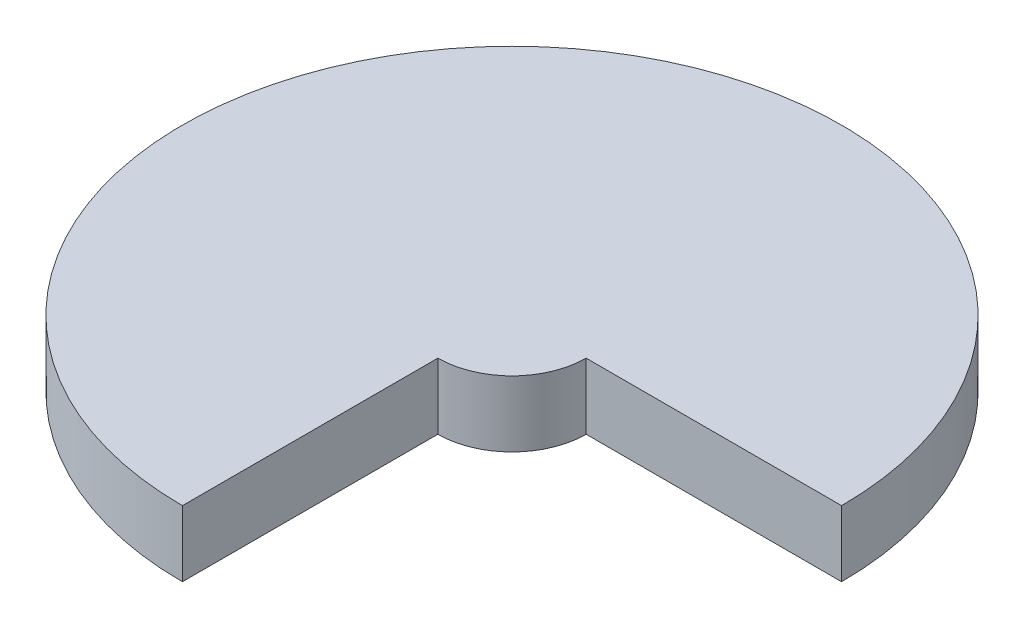
SolidWorks part; units mm, degrees
ref_plane "Front Plane" through (0, 0, 0) normal (0, 0, 1) x (1, 0, 0)
ref_plane "Top Plane" through (0, 0, 0) normal (0, 1, 0) x (1, 0, 0)
ref_plane "Right Plane" through (0, 0, 0) normal (1, 0, 0) x (0, 0, -1)
sketch "Sketch1" plane through (0, 0, 0) normal (0, 1, 0) x (1, 0, 0)
  line L0 (100, 0) -> (22.5, 0)
  line L1 (0, -22.5) -> (0, -100)
  arc A0 (100, 0) -> (0, -100) centre (0, 0) ccw
  arc A1 (0, -22.5) -> (22.5, 0) centre (0, 0) ccw
  dimension "D1" = 200
  dimension "D2" = 45
extrude "Boss-Extrude1" add sketch "Sketch1" along normal blind 20
